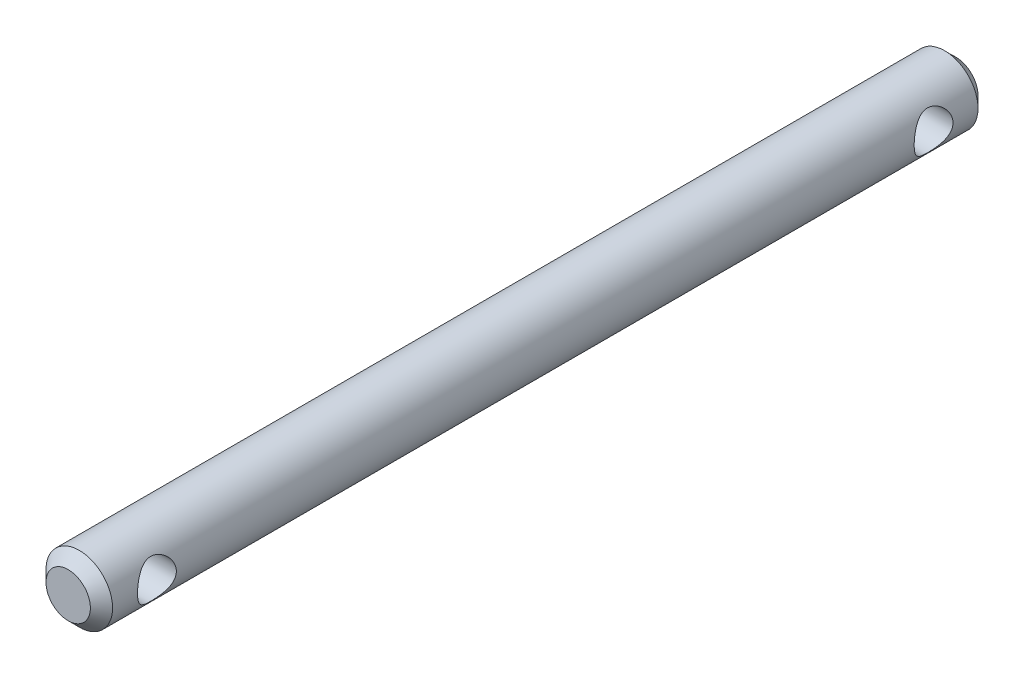
SolidWorks part; units mm, degrees
material "Сплав 2024"
ref_plane "Спереди" through (0, 0, 0) normal (0, 0, 1) x (1, 0, 0)
ref_plane "Сверху" through (0, 0, 0) normal (0, 1, 0) x (1, 0, 0)
ref_plane "Справа" through (0, 0, 0) normal (1, 0, 0) x (0, 0, -1)
sketch "Эскиз1" plane through (0, 0, 0) normal (0, 0, 1) x (1, 0, 0)
  circle A0 centre (0, 0) radius 3
  dimension "D1" = 6
extrude "Бобышка-Вытянуть1" add sketch "Эскиз1" along normal blind 5
sketch "Эскиз2" plane through (0, 0, 5) normal (0, 0, 1) x (1, 0, 0)
  circle A0 centre (0, 0) radius 3
  dimension "D1" = 6
extrude "Бобышка-Вытянуть2" add sketch "Эскиз2" along normal blind 75
ref_plane "Плоскость1" through (3, 0, 0) normal (1, 0, 0) x (0, 0, -1)
sketch "Эскиз3" plane through (3, 0, 0) normal (1, 0, 0) x (0, 0, -1)
  line L0 (-80, 0) -> (0, 0) construction
  line L2 (-80, 3) -> (-80, -3) construction
  line L3 (0, -3) -> (0, 3) construction
  line L4 (-40, 0) -> (-40, 6.0957) construction
  circle A0 centre (-75, 0) radius 1.75
  circle A1 centre (-5, 0) radius 1.75
  dimension "D1" = 3.5
  dimension "D2" = 5
extrude "Вырез-Вытянуть1" cut sketch "Эскиз3" against normal through all
chamfer "Фаска1" distance 1 angle 45 2 edges at (3, 0, 0) (3, 0, 80)
